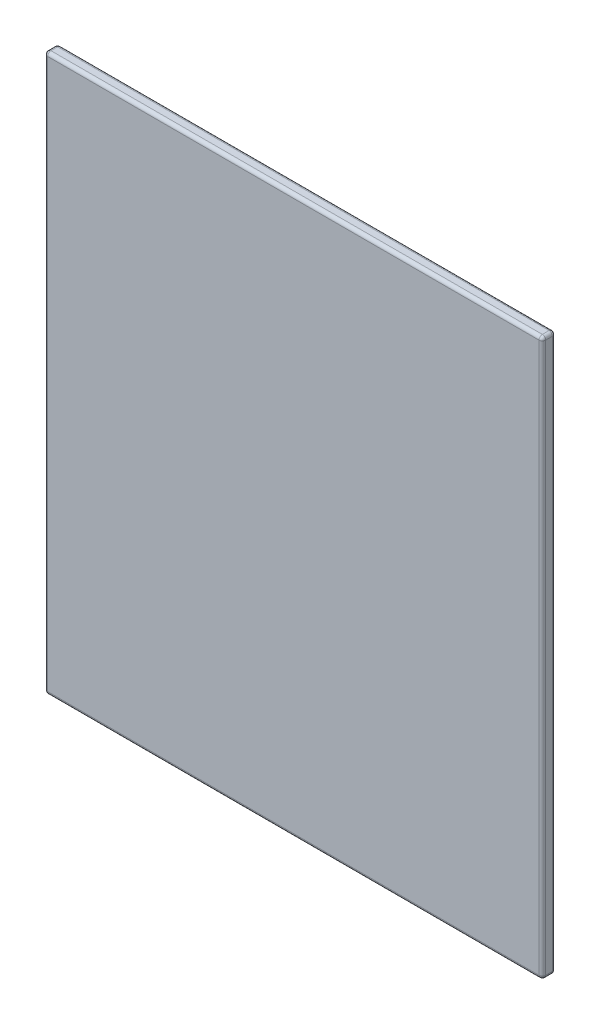
SolidWorks part; units mm, degrees
ref_plane "Front Plane" through (0, 0, 0) normal (0, 0, 1) x (1, 0, 0)
ref_plane "Top Plane" through (0, 0, 0) normal (0, 1, 0) x (1, 0, 0)
ref_plane "Right Plane" through (0, 0, 0) normal (1, 0, 0) x (0, 0, -1)
sketch "Sketch1" plane through (0, 0, 0) normal (0, 0, 1) x (1, 0, 0)
  line L1 (-37.35, -41.75) -> (37.35, -41.75)
  line L2 (-37.35, -41.75) -> (-37.35, 41.75)
  line L3 (-37.35, 41.75) -> (37.35, 41.75)
  line L4 (37.35, -41.75) -> (37.35, 41.75)
  line L5 (-37.35, -41.75) -> (37.35, 41.75) construction
  line L6 (-37.35, 41.75) -> (37.35, -41.75) construction
  point P0 (0, 0)
  dimension "D1" = 74.7
  dimension "D2" = 83.5
extrude "Boss-Extrude1" add sketch "Sketch1" along normal blind 2
fillet "Fillet1" radius 0.5 12 edges at (0, -41.75, 2) (0, -41.75, 0) (-37.35, 0, 2) (-37.35, -41.75, 1) (-37.35, 0, 0) (0, 41.75, 2) (-37.35, 41.75, 1) (0, 41.75, 0) (37.35, -41.75, 1) (37.35, 0, 2) (37.35, 41.75, 1) (37.35, 0, 0)
